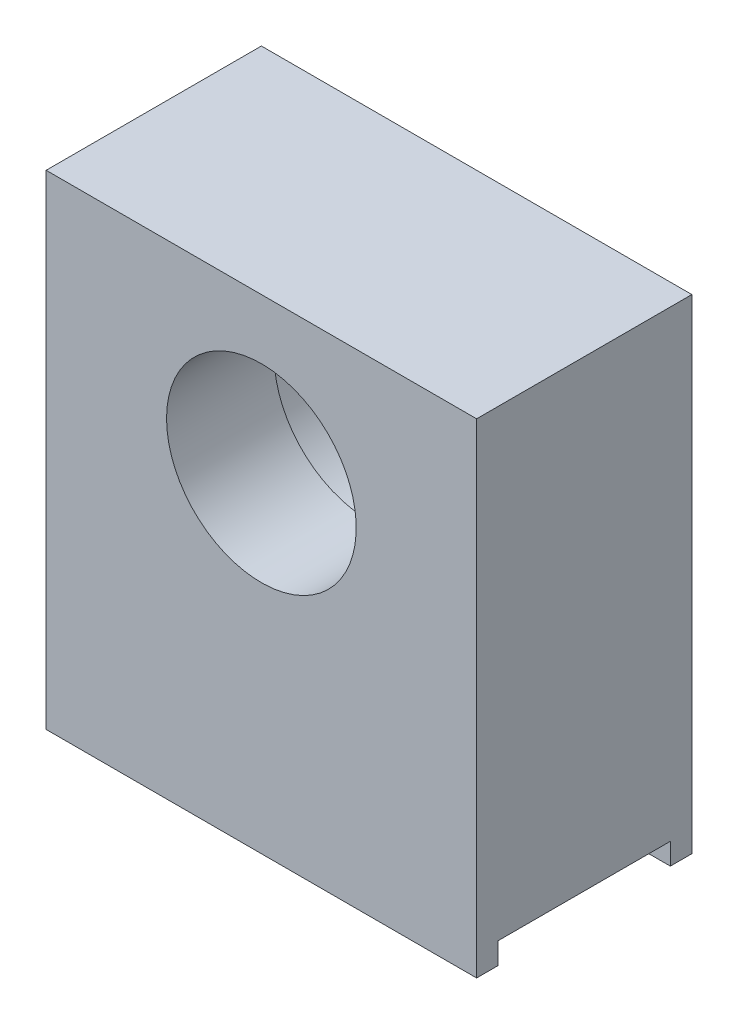
SolidWorks part; units mm, degrees
ref_plane "Front Plane" through (0, 0, 0) normal (0, 0, 1) x (1, 0, 0)
ref_plane "Top Plane" through (0, 0, 0) normal (0, 1, 0) x (1, 0, 0)
ref_plane "Right Plane" through (0, 0, 0) normal (1, 0, 0) x (0, 0, -1)
sketch "Sketch1" plane through (0, 0, 0) normal (0, 1, 0) x (1, 0, 0)
  line L1 (-14.6748, 6.8957) -> (17.3252, 6.8957)
  line L2 (-14.6748, 6.8957) -> (-14.6748, -9.1043)
  line L3 (-14.6748, -9.1043) -> (17.3252, -9.1043)
  line L4 (17.3252, 6.8957) -> (17.3252, -9.1043)
  dimension "D1" = 16
  dimension "D2" = 32
extrude "Boss-Extrude1" add sketch "Sketch1" along normal blind 36
sketch "Sketch2" plane through (0, 0, 0) normal (0, -1, 0) x (-1, 0, 0)
  line L0 (14.6748, 6.8957) -> (14.6748, -9.1043) construction
  line L1 (14.6748, 5.2957) -> (-17.3252, 5.2957)
  line L2 (14.6748, 5.2957) -> (14.6748, -7.5043)
  line L3 (14.6748, -7.5043) -> (-17.3252, -7.5043)
  line L4 (-17.3252, 5.2957) -> (-17.3252, -7.5043)
  line L5 (-17.3252, -9.1043) -> (-17.3252, 6.8957) construction
  line L6 (-17.3252, 6.8957) -> (14.6748, 6.8957) construction
  line L7 (14.6748, -9.1043) -> (-17.3252, -9.1043) construction
  dimension "D1" = 1.6
  dimension "D2" = 1.6
extrude "Cut-Extrude1" cut sketch "Sketch2" against normal blind 1.6
sketch "Sketch3" plane through (0, 0, -6.8957) normal (0, 0, -1) x (-1, 0, 0)
  line L0 (14.6748, 36) -> (14.6748, 0) construction
  line L1 (-17.3252, 0) -> (14.6748, 0) construction
  circle A0 centre (-1.3252, 24.5) radius 7.05
  dimension "D1" = 14.1
  dimension "D3" = 24.5
  dimension "D2" = 16
extrude "Cut-Extrude2" cut sketch "Sketch3" against normal through all
sketch "Sketch4" plane through (0, 0, -6.8957) normal (0, 0, -1) x (-1, 0, 0)
  circle A0 centre (-1.3252, 24.5) radius 7.7
  dimension "D1" = 15.4
extrude "Cut-Extrude3" cut sketch "Sketch4" against normal blind 8
